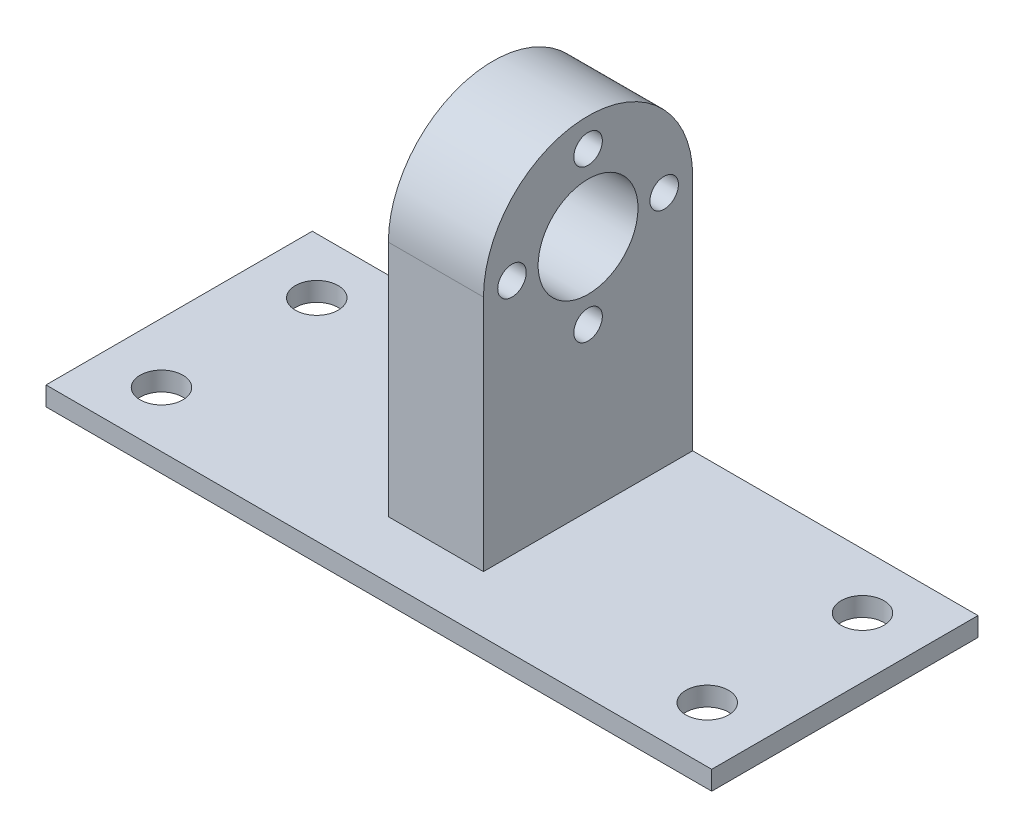
SolidWorks part; units mm, degrees
ref_plane "Front Plane" through (0, 0, 0) normal (0, 0, 1) x (1, 0, 0)
ref_plane "Top Plane" through (0, 0, 0) normal (0, 1, 0) x (1, 0, 0)
ref_plane "Right Plane" through (0, 0, 0) normal (1, 0, 0) x (0, 0, -1)
sketch "Sketch1" plane through (0, 0, 0) normal (0, 1, 0) x (1, 0, 0)
  line L1 (35, -14) -> (-35, -14)
  line L2 (35, -14) -> (35, 14)
  line L3 (35, 14) -> (-35, 14)
  line L4 (-35, -14) -> (-35, 14)
  line L5 (35, -14) -> (-35, 14) construction
  line L6 (35, 14) -> (-35, -14) construction
  point P0 (0, 0)
  dimension "D1" = 70
  dimension "D2" = 28
extrude "Boss-Extrude1" add sketch "Sketch1" along normal blind 2
sketch "Sketch2" plane through (0, 0, 0) normal (1, 0, 0) x (0, 0, -1)
  circle A0 centre (3, 27) radius 5.25
  circle A1 centre (3, 27) radius 11
  dimension "D1" = 10.5
  dimension "D2" = 22
  dimension "D3" = 25
  dimension "D4" = 11
extrude "Boss-Extrude2" add sketch "Sketch2" along normal mid plane 10 separate body
sketch "Sketch3" plane through (0, 2, 0) normal (0, 1, 0) x (1, 0, 0)
  line L1 (5, -8) -> (-5, -8)
  line L2 (5, -8) -> (5, 14)
  line L3 (5, 14) -> (-5, 14)
  line L4 (-5, -8) -> (-5, 14)
  line L5 (5, -8) -> (-5, 14) construction
  line L6 (5, 14) -> (-5, -8) construction
  point P0 (0, 3)
  point P6 (5, -4.5)
  point P7 (5, -4.5)
  point P8 (0, 0)
  point P9 (0, 0)
  point P10 (5, -8)
extrude "Boss-Extrude3" add sketch "Sketch3" along normal up to next
sketch "Sketch5" plane through (0, 2, 0) normal (0, 1, 0) x (1, 0, 0)
  circle A0 centre (-28.6924, 8.1622) radius 2.25
  point P2 (-19.8367, 8.9478)
  point P3 (-18.5021, 8.7658)
  point P4 (-28.6924, 8.1622)
extrude "Cut-Extrude1" cut sketch "Sketch5" against normal through all
ref_plane "Plane1" through (0, 0, 0) normal (-1, 0, 0) x (0, 0, 1)
ref_plane "Plane2" through (0, 0, 0) normal (0, 0, -1) x (-1, 0, 0)
mirror "Mirror1" about plane through (0, 0, 0) normal (0, 0, -1) of "Cut-Extrude1"
mirror "Mirror2" about plane through (0, 0, 0) normal (-1, 0, 0) of "Mirror1", "Cut-Extrude1"
sketch "Sketch6" plane through (-5, 0, 0) normal (-1, 0, 0) x (0, 0, 1)
  line L0 (-3, 35) -> (-3, 27) construction
  line L2 (5, 27) -> (-11, 27) construction
  line L3 (-3, 27) -> (-3, 19) construction
  circle A0 centre (-3, 27) radius 5.25 construction
  circle A1 centre (-3, 35) radius 1.5
  circle A2 centre (-11, 27) radius 1.5
  circle A3 centre (5, 27) radius 1.5
  circle A4 centre (-3, 19) radius 1.5
  point P0 (-7.7946, 29.1387)
  point P1 (-3, 27)
  point P14 (0, 0)
  dimension "D1" = 3
  dimension "D6" = 3
  dimension "D7" = 3
  dimension "D8" = 3
  dimension "D2" = 8
  dimension "D3" = 8
  dimension "D4" = 8
  dimension "D5" = 8
extrude "Cut-Extrude2" cut sketch "Sketch6" against normal through all
